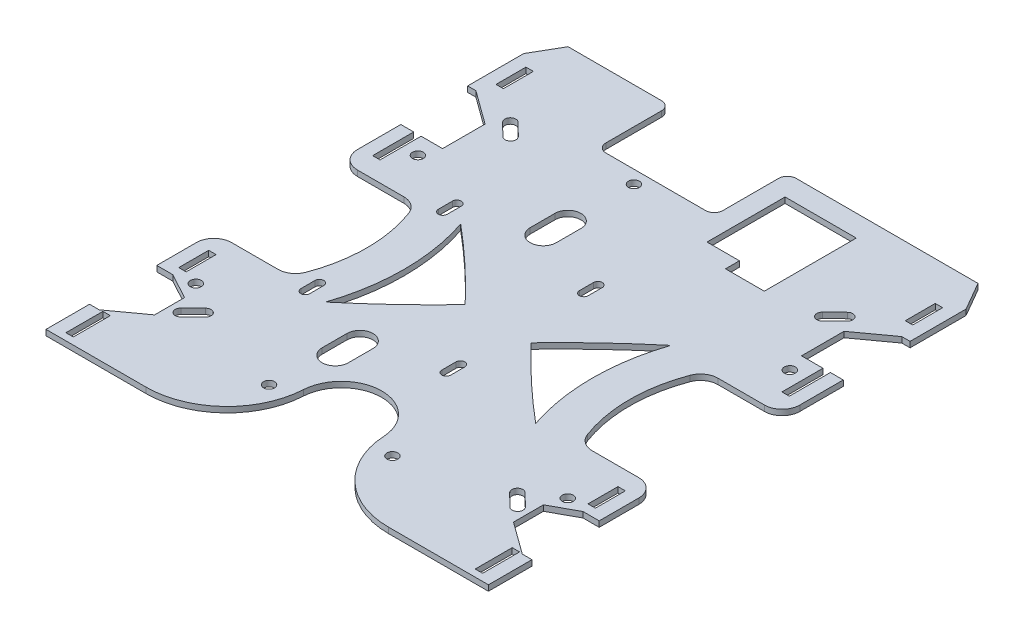
SolidWorks part; units mm, degrees
ref_plane "Front Plane" through (0, 0, 0) normal (0, 0, 1) x (1, 0, 0)
ref_plane "Top Plane" through (0, 0, 0) normal (0, 1, 0) x (1, 0, 0)
ref_plane "Right Plane" through (0, 0, 0) normal (1, 0, 0) x (0, 0, -1)
sketch "Sketch1" plane through (0, 0, 0) normal (0, 1, 0) x (1, 0, 0)
  line L0 (-1000, 0) -> (49000, 0) construction
  line L1 (0, 0) -> (0, 100.3728) construction
  line L5 (-62.75, -55) -> (-34.3696, -55)
  line L6 (62.75, -55) -> (34.3696, -55)
  line L7 (9.55, 82.35) -> (29.75, 82.35)
  line L8 (29.75, 82.35) -> (29.75, 56.25)
  line L10 (9.55, 60.2) -> (9.55, 82.35)
  line L11 (57, 77.5) -> (59.1, 77.5)
  line L12 (59.1, 77.5) -> (59.1, 69)
  line L13 (59.1, 69) -> (57, 69)
  line L14 (57, 69) -> (57, 77.5)
  line L15 (57, 39) -> (57, 47.5)
  line L16 (57, 47.5) -> (59.1, 47.5)
  line L17 (59.1, 47.5) -> (59.1, 39)
  line L18 (59.1, 39) -> (57, 39)
  line L19 (57, 9) -> (57, 17.5) construction
  line L20 (57, 17.5) -> (59.1, 17.5) construction
  line L21 (59.1, 17.5) -> (59.1, 9) construction
  line L22 (59.1, 9) -> (57, 9) construction
  line L35 (57, -51) -> (57, -42.5)
  line L36 (57, -42.5) -> (59.1, -42.5)
  line L37 (59.1, -42.5) -> (59.1, -51)
  line L38 (-62.75, -55) -> (-62.75, 0)
  line L39 (9.55, 60.2) -> (18.75, 60.2)
  line L40 (59.1, -51) -> (57, -51)
  line L42 (18.75, 56.25) -> (18.75, 60.2)
  line L43 (-59.1, -51) -> (-59.1, -42.5)
  line L44 (-59.1, -42.5) -> (-57, -42.5)
  line L45 (-62.75, 0) -> (-62.75, 80.5)
  line L46 (62.75, -55) -> (62.75, 0)
  line L47 (62.75, 0) -> (62.75, 80.5)
  line L48 (-62.75, 80.5) -> (-58.1408, 88.4834)
  line L49 (-58.1408, 88.4834) -> (58.1408, 88.4834)
  line L50 (62.75, 80.5) -> (58.1408, 88.4834)
  line L51 (57, -21) -> (57, -12.5)
  line L52 (57, -12.5) -> (59.1, -12.5)
  line L53 (59.1, -12.5) -> (59.1, -21)
  line L54 (59.1, -21) -> (57, -21)
  line L55 (57, 69) -> (57, 39) construction
  line L56 (-59.1, 69) -> (-59.1, 77.5)
  line L57 (-59.1, 77.5) -> (-57, 77.5)
  line L58 (-57, 77.5) -> (-57, 69)
  line L59 (-57, 69) -> (-59.1, 69)
  line L60 (-59.1, 39) -> (-59.1, 47.5)
  line L61 (-59.1, 47.5) -> (-57, 47.5)
  line L62 (-57, 47.5) -> (-57, 39)
  line L63 (-57, 39) -> (-59.1, 39)
  line L64 (-59.1, 9) -> (-59.1, 17.5) construction
  line L65 (-59.1, 17.5) -> (-57, 17.5) construction
  line L66 (-57, 17.5) -> (-57, 9) construction
  line L67 (-57, 9) -> (-59.1, 9) construction
  line L68 (-59.1, -21) -> (-59.1, -12.5)
  line L69 (-59.1, -12.5) -> (-57, -12.5)
  line L70 (-57, -12.5) -> (-57, -21)
  line L71 (-57, -21) -> (-59.1, -21)
  line L72 (18.75, 56.25) -> (29.75, 56.25)
  line L74 (-57, -42.5) -> (-57, -51)
  line L75 (-57, -51) -> (-59.1, -51)
  circle A2 centre (-15, 64.0223) radius 1.55
  circle A3 centre (-17.5, -36.9777) radius 1.55
  circle A6 centre (17.5, -36.9777) radius 1.55
  arc A7 (-11.4407, -33.3184) -> (-34.3696, -55) centre (-34.3696, -32.0353) cw
  arc A8 (-11.4407, -33.3184) -> (0, -22.5) centre (0, -33.9586) cw
  arc A9 (11.4407, -33.3184) -> (34.3696, -55) centre (34.3696, -32.0353) ccw
  arc A10 (11.4407, -33.3184) -> (0, -22.5) centre (0, -33.9586) ccw
  circle A11 centre (52.75, 40.5) radius 2.75 construction
  circle A12 centre (52.75, 40.5) radius 1.55
  circle A13 centre (52.75, -22.5) radius 1.55
  circle A14 centre (52.75, -22.5) radius 2.75 construction
  circle A15 centre (-52.75, 40.5) radius 1.55
  circle A16 centre (-52.75, -22.5) radius 1.55
  circle A17 centre (-52.75, 40.5) radius 2.75 construction
  circle A18 centre (-52.75, -22.5) radius 2.75 construction
  circle A19 centre (-46, 60) radius 1.55
  circle A20 centre (46, 60) radius 1.55
  circle A21 centre (46, -30) radius 1.55
  circle A22 centre (-46, -30) radius 1.55
  point P20 (-62.75, 0)
  point P23 (0, 55)
  point P26 (62.75, 0)
  point P63 (24.25, 56.25)
  point P83 (0, 88.4834)
  dimension "D20" = 5.5
  dimension "D21" = 3.1
  dimension "D22" = 105.5
  dimension "D4" = 101
  dimension "D5" = 17.5
  dimension "D6" = 15
  dimension "D7" = 64.0223
  dimension "D8" = 120
  dimension "D9" = 55
  dimension "D10" = 2
  dimension "D11" = 5
  dimension "D12" = 2.1
  dimension "D13" = 80.5
  dimension "D14" = 125.5
  dimension "D15" = 8.5
  dimension "D16" = 77.5
  dimension "D17" = 30
  dimension "D18" = 114
  dimension "D19" = 22.5
  dimension "D23" = 4.25
  dimension "D24" = 40.5
  dimension "D25" = 22.5
  dimension "D26" = 9.55
  dimension "D27" = 29.75
  dimension "D28" = 82.35
  dimension "D29" = 3.95
  dimension "D30" = 9.2
  dimension "D31" = 26.1
  dimension "D32" = 92
  dimension "D33" = 90
  dimension "D34" = 60
extrude "主结构和连接" add sketch "Sketch1" along normal blind 1.6
sketch "外部切除点示意-1" plane through (0, 0, 0) normal (0, 1, 0) x (1, 0, 0)
  line L0 (-58.1408, 88.4834) -> (58.1408, 88.4834) construction
  line L1 (0, 0) -> (-149.6598, 0) construction
  line L2 (0, -1000) -> (0, 49000) construction
  line L3 (-41.25, 28.3195) -> (-41.2859, -7.3505) construction
  line L4 (41.25, 28.3195) -> (41.2859, -7.3505) construction
  line L5 (4.0667, 88.4834) -> (4.0667, 67.7334)
  line L6 (-41.25, 28.3195) -> (-62.75, 28.3195)
  line L7 (4.0667, 67.7334) -> (-29.1468, 67.7334)
  line L8 (-29.1468, 67.7334) -> (-29.1468, 88.4834)
  line L10 (-29.1468, 88.4834) -> (4.0667, 88.4834)
  line L11 (-62.75, 0) -> (-62.75, 80.5) construction
  line L12 (-62.75, 28.3195) -> (-62.75, -7.3505)
  line L13 (-62.75, -55) -> (-62.75, 0) construction
  line L14 (-62.75, -7.3505) -> (-41.2859, -7.3505)
  line L15 (41.25, 28.3195) -> (62.75, 28.3195)
  line L16 (62.75, 28.3195) -> (62.75, -7.3505)
  line L17 (62.75, -7.3505) -> (41.2859, -7.3505)
  line L18 (-62.0244, -25.5795) -> (-62.75, -26.1067) construction
  line L19 (60.406, 64.6074) -> (50.9062, 57.7054)
  line L20 (-62.75, -26.1067) -> (-62.75, -41.5627) construction
  line L21 (-60.4273, -42.3422) -> (-53.5015, -37.3103) construction
  line L22 (-53.3356, -36.2627) -> (-53.6571, -35.8201) construction
  line L23 (-61.7688, -41.7717) -> (-61.4749, -42.1762) construction
  line L24 (-60.6553, -26.188) -> (-60.9768, -25.7455) construction
  line L25 (-62.75, 62.6074) -> (-62.75, 47.1514) construction
  line L26 (62.75, 64.6074) -> (60.406, 64.6074)
  line L27 (-62.75, 47.1514) -> (-62.0244, 46.6242) construction
  line L28 (-60.6553, 47.2327) -> (-60.9768, 46.7901) construction
  line L29 (-53.3356, 57.3074) -> (-53.6571, 56.8648) construction
  line L30 (-53.5015, 58.355) -> (-60.4273, 63.3868) construction
  line L31 (-61.4749, 63.2209) -> (-61.7688, 62.8164) construction
  line L32 (-62.75, 64.6074) -> (-60.406, 64.6074)
  line L33 (-60.406, 64.6074) -> (-50.9062, 57.7054)
  line L34 (-50.9062, 57.7054) -> (-50.9062, 45.6514)
  line L35 (-50.9062, 45.6514) -> (-62.75, 45.6514)
  line L36 (-62.75, 45.6514) -> (-62.75, 64.6074)
  line L37 (-62.75, -23.5795) -> (-58.187, -23.5795)
  line L38 (-58.187, -23.5795) -> (-50.9062, -27.5482)
  line L39 (-50.9062, -27.5482) -> (-50.9062, -36.0427)
  line L41 (-62.75, -42.6524) -> (-62.75, -23.5795)
  line L42 (-50.9062, -36.0427) -> (-60.0037, -42.6524)
  line L43 (-60.0037, -42.6524) -> (-62.75, -42.6524)
  line L44 (62.75, 45.6514) -> (62.75, 64.6074)
  line L45 (50.9062, 45.6514) -> (62.75, 45.6514)
  line L46 (50.9062, 57.7054) -> (50.9062, 45.6514)
  line L47 (62.75, -23.5795) -> (58.187, -23.5795)
  line L48 (62.75, -42.6524) -> (62.75, -23.5795)
  line L49 (60.0037, -42.6524) -> (62.75, -42.6524)
  line L50 (50.9062, -36.0427) -> (60.0037, -42.6524)
  line L51 (50.9062, -27.5482) -> (50.9062, -36.0427)
  line L52 (58.187, -23.5795) -> (50.9062, -27.5482)
  arc A0 (-41.25, 28.3195) -> (-41.2859, -7.3505) centre (-78.8424, 10.5223) cw
  arc A1 (-61.7688, 62.8164) -> (-62.75, 62.6074) centre (-62.3756, 63.2573) cw construction
  arc A3 (41.25, 28.3195) -> (41.2859, -7.3505) centre (78.8424, 10.5223) ccw
  arc A4 (-61.4749, 63.2209) -> (-60.4273, 63.3868) centre (-60.8681, 62.7801) cw construction
  arc A5 (-53.5015, 58.355) -> (-53.3356, 57.3074) centre (-53.9424, 57.7482) cw construction
  arc A6 (-53.5636, 55.877) -> (-53.6571, 56.8648) centre (-53.0504, 56.4239) cw construction
  arc A7 (-53.5636, 55.877) -> (-59.687, 47.449) centre (-57.1562, 52.0488) cw construction
  arc A8 (-60.6553, 47.2327) -> (-59.687, 47.449) centre (-60.0485, 46.7919) cw construction
  arc A9 (-62.0244, 46.6242) -> (-60.9768, 46.7901) centre (-61.5836, 47.231) ccw construction
  arc A10 (-62.0244, -25.5795) -> (-60.9768, -25.7455) centre (-61.5836, -26.1863) cw construction
  arc A11 (-60.6553, -26.188) -> (-59.687, -26.4043) centre (-60.0485, -25.7472) ccw construction
  arc A12 (-59.687, -26.4043) -> (-53.5636, -34.8324) centre (-57.1562, -31.0041) cw construction
  arc A13 (-53.5636, -34.8324) -> (-53.6571, -35.8201) centre (-53.0504, -35.3793) ccw construction
  arc A14 (-53.3356, -36.2627) -> (-53.5015, -37.3103) centre (-53.9424, -36.7035) cw construction
  arc A15 (-61.7688, -41.7717) -> (-62.75, -41.5627) centre (-62.3756, -42.2126) ccw construction
  arc A17 (-61.4749, -42.1762) -> (-60.4273, -42.3422) centre (-60.8681, -41.7354) ccw construction
  circle A18 centre (-52.75, -22.5) radius 2.75 construction
  dimension "D3" = 6.25
  dimension "D7" = 6.25
  dimension "D1" = 20.75
  dimension "D2" = 1
  dimension "D4" = 1.5
  dimension "D5" = 2
  dimension "D6" = 0.5
  dimension "D8" = 3.55
  dimension "D9" = 2
  dimension "D10" = 1.5
extrude "底板让位" cut sketch "外部切除点示意-1" along normal through all
fillet "Fillet1" radius 5 8 edges at (62.75, 0.8, -28.3195) (62.75, 0.8, 7.3505) (41.2859, 0.8, 7.3505) (41.25, 0.8, -28.3195) (-62.75, 0.8, 7.3505) (-62.75, 0.8, -28.3195) (-41.2859, 0.8, 7.3505) (-41.25, 0.8, -28.3195)
sketch "Sketch2" plane through (0, 1.6, 0) normal (0, 1, 0) x (1, 0, 0)
  line L0 (-57, -51) -> (-57, -53)
  line L1 (-57, -53) -> (-59.1, -53)
  line L2 (-59.1, -53) -> (-59.1, -51)
  line L3 (-59.1, -51) -> (-57, -51)
  line L4 (-59.1, 39) -> (-59.1, 34)
  line L5 (-59.1, 34) -> (-57, 34)
  line L6 (-57, 34) -> (-57, 39)
  line L7 (-57, 39) -> (-59.1, 39)
  line L8 (0, 0) -> (0, -97.4758) construction
  line L9 (59.1, -53) -> (59.1, -51)
  line L10 (57, -53) -> (59.1, -53)
  line L11 (57, -51) -> (57, -53)
  line L12 (59.1, -51) -> (57, -51)
  line L13 (57, 34) -> (57, 39)
  line L14 (59.1, 34) -> (57, 34)
  line L15 (59.1, 39) -> (59.1, 34)
  line L16 (57, 39) -> (59.1, 39)
  dimension "D1" = 5
  dimension "D2" = 2
extrude "榫卯额外补强" cut sketch "Sketch2" against normal through all
sketch "电源模块接口-草图" plane through (0, 0, 0) normal (0, 1, 0) x (1, 0, 0)
  line L4 (-15.3656, 45.6643) -> (-15.3656, 38.6643) construction
  line L7 (-11.6656, 45.6643) -> (-11.6656, 38.6643)
  line L8 (-19.0656, 45.6643) -> (-19.0656, 38.6643)
  line L9 (-15.3656, -13.3357) -> (-15.3656, -20.3357) construction
  line L12 (-11.6656, -13.3357) -> (-11.6656, -20.3357)
  line L15 (-19.0656, -13.3357) -> (-19.0656, -20.3357)
  line L16 (-15.3656, -13.3357) -> (-15.3656, 38.6643) construction
  line L18 (4.6344, 34.1643) -> (4.6344, 30.1643) construction
  line L19 (5.8844, 34.1643) -> (5.8844, 30.1643)
  line L20 (3.3844, 34.1643) -> (3.3844, 30.1643)
  line L21 (4.6344, -8.8357) -> (4.6344, -4.8357) construction
  line L24 (-15.3656, 12.6643) -> (18.8472, 12.6643) construction
  line L25 (5.8844, -8.8357) -> (5.8844, -4.8357)
  line L26 (3.3844, -8.8357) -> (3.3844, -4.8357)
  line L27 (-35.3656, 34.1643) -> (-35.3656, 30.1643) construction
  line L28 (-36.6156, 34.1643) -> (-36.6156, 30.1643)
  line L29 (-34.1156, 34.1643) -> (-34.1156, 30.1643)
  line L30 (-35.3656, -8.8357) -> (-35.3656, -4.8357) construction
  line L31 (-36.6156, -8.8357) -> (-36.6156, -4.8357)
  line L32 (-34.1156, -8.8357) -> (-34.1156, -4.8357)
  arc A8 (-11.6656, 45.6643) -> (-19.0656, 45.6643) centre (-15.3656, 45.6643) ccw
  arc A9 (-19.0656, 38.6643) -> (-11.6656, 38.6643) centre (-15.3656, 38.6643) ccw
  arc A10 (-11.6656, -13.3357) -> (-19.0656, -13.3357) centre (-15.3656, -13.3357) ccw
  arc A11 (-19.0656, -20.3357) -> (-11.6656, -20.3357) centre (-15.3656, -20.3357) ccw
  arc A12 (5.8844, 34.1643) -> (3.3844, 34.1643) centre (4.6344, 34.1643) ccw
  arc A13 (3.3844, 30.1643) -> (5.8844, 30.1643) centre (4.6344, 30.1643) ccw
  arc A16 (5.8844, -8.8357) -> (3.3844, -8.8357) centre (4.6344, -8.8357) cw
  arc A17 (3.3844, -4.8357) -> (5.8844, -4.8357) centre (4.6344, -4.8357) cw
  arc A18 (-36.6156, 34.1643) -> (-34.1156, 34.1643) centre (-35.3656, 34.1643) cw
  arc A19 (-34.1156, 30.1643) -> (-36.6156, 30.1643) centre (-35.3656, 30.1643) cw
  arc A20 (-36.6156, -8.8357) -> (-34.1156, -8.8357) centre (-35.3656, -8.8357) ccw
  arc A21 (-34.1156, -4.8357) -> (-36.6156, -4.8357) centre (-35.3656, -4.8357) ccw
  point P2 (-15.3656, 42.1643)
  point P7 (-15.3656, -16.8357)
  point P18 (4.6344, 32.1643)
  point P25 (4.6344, -6.8357)
  point P35 (-35.3656, 32.1643)
  point P42 (-35.3656, -6.8357)
  dimension "D3" = 1.25
  dimension "D2" = 3.7
  dimension "D1" = 52
  dimension "D4" = 35
  dimension "D5" = 66
  dimension "D6" = 4
  dimension "D7" = 20
extrude "电源模块接口" cut sketch "电源模块接口-草图" along normal through all
sketch "草图2" plane through (0, 1.6, 0) normal (0, 1, 0) x (1, 0, 0)
  line L0 (0, 0) -> (0, 53.6886) construction
  line L1 (0, 0) -> (0, 100.3728) construction
  line L2 (0, 0) -> (139.6377, 0) construction
  line L3 (-201000, 0) -> (249000, 0) construction
  line L4 (0, 19.8942) -> (0, 10.5223) construction
  line L5 (0, 10.5223) -> (9.3719, 10.5223) construction
  arc A3 (9.3719, 10.5223) -> (29.8202, 29.7013) centre (187.9553, -159.3904) cw
  arc A4 (29.8202, 29.7013) -> (29.8202, -8.6566) centre (87.1283, 10.5223) ccw
  arc A5 (29.8202, -8.6566) -> (9.3719, 10.5223) centre (187.9553, 180.4351) cw
  circle A6 centre (0, 10.5223) radius 9.3719 construction
  arc A7 (0, 1.1505) -> (19.1789, -19.2978) centre (-169.9128, -177.433) cw construction
  arc A8 (19.1789, -19.2978) -> (-19.1789, -19.2978) centre (0, -76.6059) ccw construction
  arc A9 (-19.1789, -19.2978) -> (0, 1.1505) centre (169.9128, -177.433) cw construction
  arc A10 (-9.3719, 10.5223) -> (-29.8202, -8.6566) centre (-187.9553, 180.4351) cw
  arc A11 (-29.8202, -8.6566) -> (-29.8202, 29.7013) centre (-87.1283, 10.5223) ccw
  arc A12 (-29.8202, 29.7013) -> (-9.3719, 10.5223) centre (-187.9553, -159.3904) cw
  arc A13 (0, 19.8942) -> (-19.1789, 40.3425) centre (169.9128, 198.4777) cw construction
  arc A14 (-19.1789, 40.3425) -> (19.1789, 40.3425) centre (0, 97.6506) ccw construction
  arc A15 (19.1789, 40.3425) -> (0, 19.8942) centre (-169.9128, 198.4777) cw construction
  point P38 (0, 10.5223)
  dimension "D1" = 10.5223
  dimension "D2" = 4
extrude "飞控走线" cut sketch "草图2" against normal blind 10
sketch "Sketch3" plane through (0, 1.6, 0) normal (0, 1, 0) x (1, 0, 0)
  line L0 (-46, 60) -> (46, -30) construction
  line L1 (-46, 60) -> (-40.4597, 65.6634) construction
  line L2 (-47.7871, 61.7482) -> (-44.2129, 58.2518) construction
  line L3 (-46.7032, 62.8562) -> (-43.129, 59.3598)
  line L4 (-48.871, 60.6402) -> (-45.2968, 57.1438)
  line L5 (0, 0) -> (0, 80.8539) construction
  line L6 (0, 0) -> (0, 100.3728) construction
  line L7 (-46, -30) -> (46, 60) construction
  line L8 (-47.7871, -31.7482) -> (-44.2129, -28.2518) construction
  line L9 (-48.871, -30.6402) -> (-45.2968, -27.1438)
  line L10 (-46.7032, -32.8562) -> (-43.129, -29.3598)
  line L11 (47.7871, -31.7482) -> (44.2129, -28.2518) construction
  line L12 (48.871, -30.6402) -> (45.2968, -27.1438)
  line L13 (46.7032, -32.8562) -> (43.129, -29.3598)
  line L14 (47.7871, 61.7482) -> (44.2129, 58.2518) construction
  line L15 (46.7032, 62.8562) -> (43.129, 59.3598)
  line L16 (48.871, 60.6402) -> (45.2968, 57.1438)
  arc A0 (-46.7032, 62.8562) -> (-48.871, 60.6402) centre (-47.7871, 61.7482) ccw
  arc A1 (-45.2968, 57.1438) -> (-43.129, 59.3598) centre (-44.2129, 58.2518) ccw
  arc A3 (-48.871, -30.6402) -> (-46.7032, -32.8562) centre (-47.7871, -31.7482) ccw
  arc A4 (-43.129, -29.3598) -> (-45.2968, -27.1438) centre (-44.2129, -28.2518) ccw
  arc A6 (48.871, -30.6402) -> (46.7032, -32.8562) centre (47.7871, -31.7482) cw
  arc A7 (43.129, -29.3598) -> (45.2968, -27.1438) centre (44.2129, -28.2518) cw
  arc A8 (46.7032, 62.8562) -> (48.871, 60.6402) centre (47.7871, 61.7482) cw
  arc A9 (45.2968, 57.1438) -> (43.129, 59.3598) centre (44.2129, 58.2518) cw
  point P7 (-46, 60)
  point P23 (-46, -30)
  point P31 (46, -30)
  point P38 (46, 60)
  dimension "D1" = 1.55
  dimension "D3" = 1.55
  dimension "D2" = 5
extrude "NUC接口扩口" cut sketch "Sketch3" against normal through all
fillet "圆角1" radius 2.5 4 edges at (-29.1468, 0.8, -67.7334) (4.0667, 0.8, -67.7334) (4.0667, 0.8, -88.4834) (-29.1468, 0.8, -88.4834)
